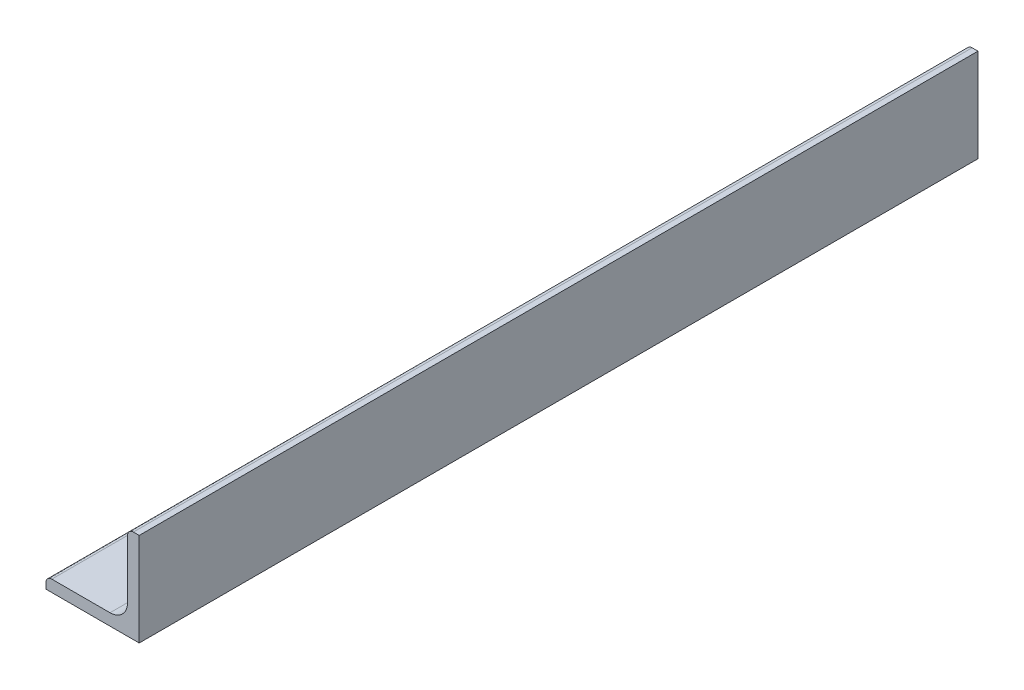
SolidWorks part; units mm, degrees
ref_plane "Front Plane" through (0, 0, 0) normal (0, 0, 1) x (1, 0, 0)
ref_plane "Top Plane" through (0, 0, 0) normal (0, 1, 0) x (1, 0, 0)
ref_plane "Right Plane" through (0, 0, 0) normal (1, 0, 0) x (0, 0, -1)
sketch "Sketch0" plane through (0, 0, 0) normal (0, 0, 1) x (1, 0, 0)
  line L0 (-12.7, -12.7) -> (12.7, -12.7)
  line L1 (12.7, -12.7) -> (12.7, 12.7)
  line L2 (12.7, 0) -> (0, 0) construction
  line L3 (0, 0) -> (0, -12.7) construction
  line L4 (9.525, -4.7498) -> (9.525, 12.7) construction
  line L5 (4.7498, -9.525) -> (-12.7, -9.525) construction
  arc A0 (9.525, -4.7498) -> (4.7498, -9.525) centre (4.7498, -4.7498) cw
  point P3 (8.1264, -8.1264)
  dimension "Inside Corner Radius" = 4.7752
  dimension "Outside Height" = 25.4
  dimension "Inside Height" = 22.225
  dimension "Inside Width" = 22.225
  dimension "Wall Thickness" = 3.175
  dimension "D1" = 3.175
  dimension "Outside Width" = 25.4
sketch "Sketch1" plane through (0, 0, 0) normal (1, 0, 0) x (0, 0, -1)
  line L0 (114.3, 0) -> (-114.3, 0)
  point P4 (0, 0)
  dimension "Length" = 228.6
sketch "Sketch2" plane through (0, 0, 0) normal (0, 0, 1) x (1, 0, 0)
  line L0 (-12.7, -12.7) -> (12.7, -12.7)
  line L1 (12.7, -12.7) -> (12.7, 12.7)
  line L2 (12.7, 12.7) -> (9.525, 12.7) construction
  line L3 (9.525, 11.1125) -> (9.525, -4.7498)
  line L4 (4.7498, -9.525) -> (-11.1125, -9.525)
  line L5 (-12.7, -12.7) -> (-12.7, -9.525) construction
  line L6 (11.1125, 12.7) -> (12.7, 12.7)
  line L7 (-12.7, -11.1125) -> (-12.7, -12.7)
  line L8 (12.7, 0) -> (0, 0) construction
  line L9 (0, 0) -> (0, -12.7) construction
  arc A0 (9.525, 11.1125) -> (11.1125, 12.7) centre (11.1125, 11.1125) cw
  arc A1 (-12.7, -11.1125) -> (-11.1125, -9.525) centre (-11.1125, -11.1125) cw
  arc A2 (9.525, -4.7498) -> (4.7498, -9.525) centre (4.7498, -4.7498) cw
  dimension "Inside Radius" = 4.7752
  dimension "Height" = 25.4
  dimension "Width" = 25.4
  dimension "Thickness" = 3.175
extrude "Boss-Extrude1" add sketch "Sketch2" along normal mid plane 228.6
sketch "Break Locations" plane through (0, 0, 0) normal (1, 0, 0) x (0, 0, -1)
  line L0 (-88.392, 0) -> (88.392, 0)
  line L1 (-114.3, -12.7) -> (-114.3, 12.7) construction
  line L2 (114.3, -12.7) -> (114.3, 12.7) construction
  point P0 (-92.71, 0)
  point P1 (92.71, 0)
  point P10 (0, 0)
  point P11 (88.392, 0)
  point P13 (-88.392, 0)
  dimension "D1" = 21.59
  dimension "D2" = 21.59
  dimension "D3" = 25.908
equation "\"D1@Break Locations\" = .85 * \"Height@Sketch2\""
equation "\"D2@Break Locations\"=\"D1@Break Locations\""
equation "\"Thickness@Sketch2\"=\"wall thickness@sketch0\""
equation "\"Height@Sketch2\"=\"outside height@sketch0\""
equation "\"Width@Sketch2\"=\"outside width@sketch0\""
equation "\"Inside Radius@Sketch2\"=\"inside corner radius@sketch0\""
equation "\"Length@Boss-Extrude1\"=\"length@sketch1\""
equation "\"D3@Break Locations\"=\"D2@Break Locations\"*1.2"
equation "\"D1@Sketch0\"=\"Wall Thickness@Sketch0\""
